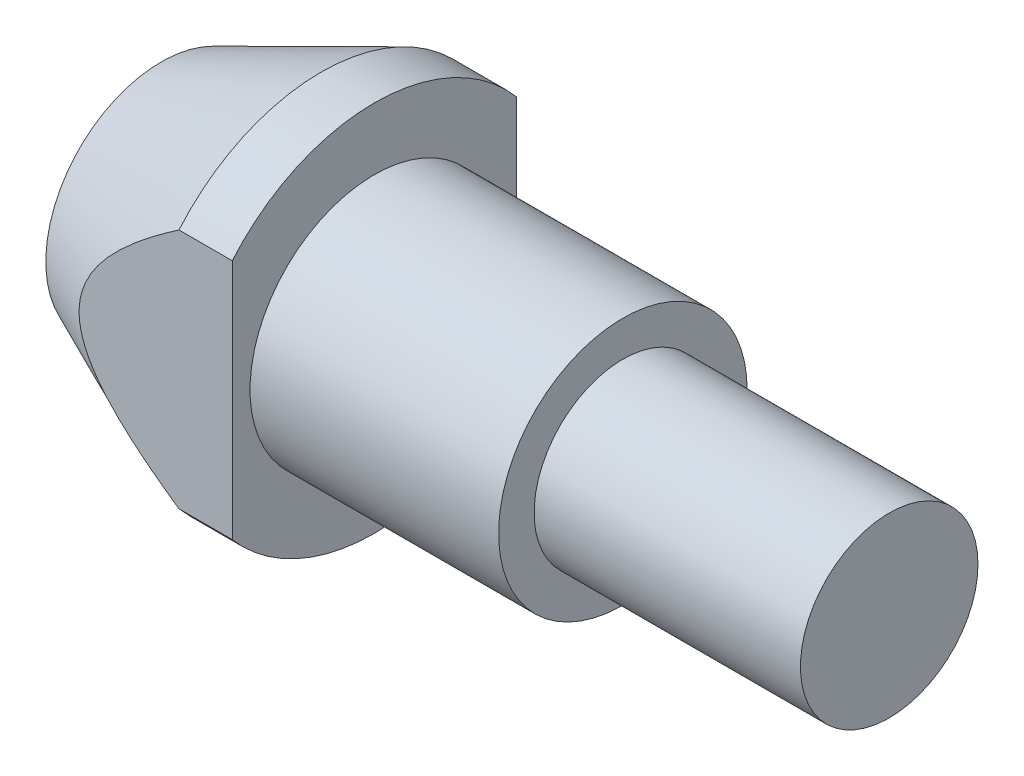
SolidWorks part; units mm, degrees
ref_plane "Front" through (0, 0, 0) normal (0, 0, 1) x (1, 0, 0)
ref_plane "Top" through (0, 0, 0) normal (0, 1, 0) x (1, 0, 0)
ref_plane "Right" through (0, 0, 0) normal (1, 0, 0) x (0, 0, -1)
sketch "Sketch1" plane through (0, 0, 0) normal (0, 0, 1) x (1, 0, 0)
  line L0 (0, 0) -> (-4.2239, 0) construction
  line L1 (-1.778, 0.889) -> (0, 0.889)
  line L2 (0, 0.889) -> (0, 0.635)
  line L3 (0, 0.635) -> (1.905, 0.635)
  line L4 (1.905, 0.635) -> (1.905, 0)
  line L5 (1.905, 0) -> (-3.302, 0)
  line L6 (-3.302, 0) -> (-3.302, 0.8255)
  line L7 (-3.302, 0.8255) -> (-2.159, 1.3335)
  line L8 (-2.159, 1.3335) -> (-1.778, 1.3335)
  line L9 (-1.778, 1.3335) -> (-1.778, 0.889)
  dimension "D1" = 1.905
  dimension "D2" = 1.778
  dimension "D3" = 1.524
  dimension "D4" = 0.381
  dimension "D5" = 1.27
  dimension "D6" = 1.778
  dimension "D7" = 1.651
  dimension "D8" = 2.667
revolve "Revolve1" add sketch "Sketch1" angle 360 about L0
sketch "Sketch2" plane through (-1.778, 0, 0) normal (1, 0, 0) x (0, 0, -1)
  line L0 (0, 0) -> (0, -0.429) construction
  line L1 (-1.5783, 1.0711) -> (-1.016, 1.0711)
  line L2 (-1.5783, 1.0711) -> (-1.5783, -1.2211)
  line L3 (-1.5783, -1.2211) -> (-1.016, -1.2211)
  line L4 (-1.016, 1.0711) -> (-1.016, -1.2211)
  line L5 (1.016, 1.0711) -> (1.016, -1.2211)
  line L6 (1.5783, -1.2211) -> (1.016, -1.2211)
  line L7 (1.5783, 1.0711) -> (1.5783, -1.2211)
  line L8 (1.5783, 1.0711) -> (1.016, 1.0711)
  dimension "D1" = 2.032
extrude "Cut-Extrude1" cut sketch "Sketch2" against normal through all
